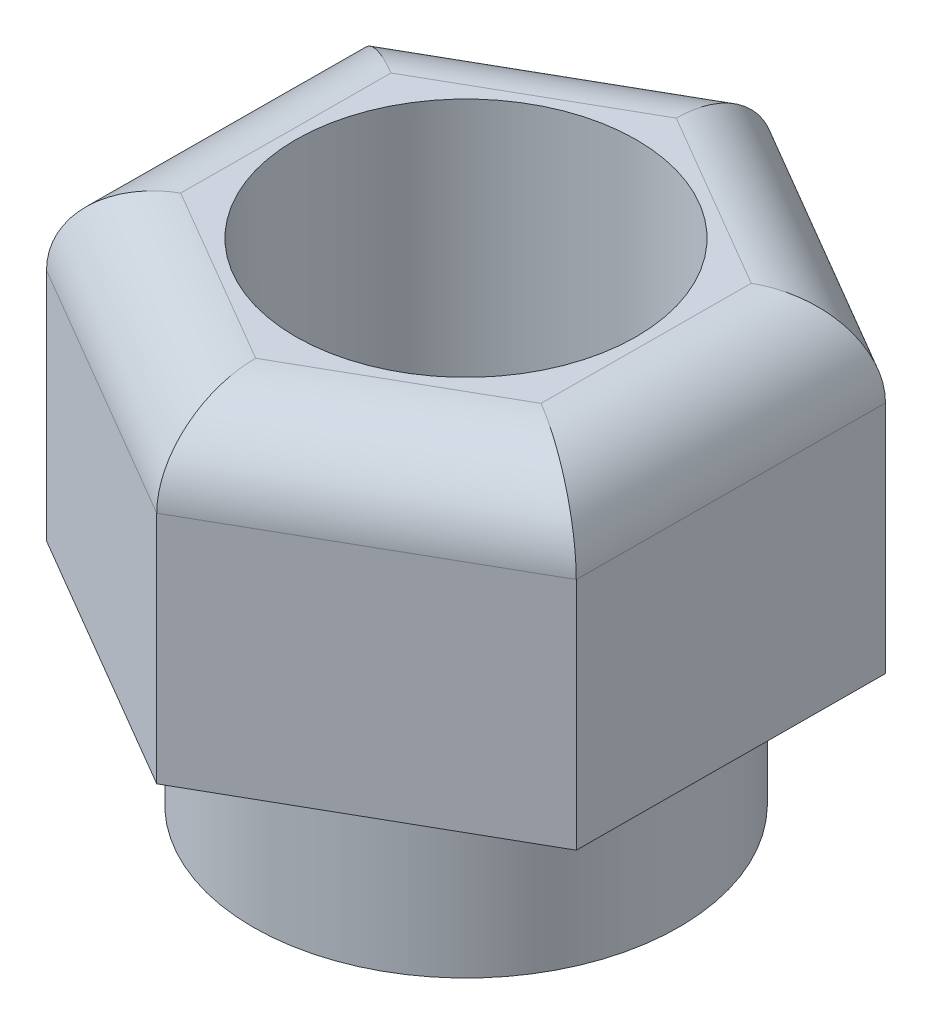
SolidWorks part; units mm, degrees
ref_plane "Front Plane" through (0, 0, 0) normal (0, 0, 1) x (1, 0, 0)
ref_plane "Top Plane" through (0, 0, 0) normal (0, 1, 0) x (1, 0, 0)
ref_plane "Right Plane" through (0, 0, 0) normal (1, 0, 0) x (0, 0, -1)
sketch "Sketch1" plane through (0, 0, 0) normal (0, 1, 0) x (1, 0, 0)
  circle A0 centre (0, 0) radius 10
  dimension "D1" = 20
extrude "Boss-Extrude1" add sketch "Sketch1" along normal blind 8
sketch "Sketch2" plane through (0, 8, 0) normal (0, 1, 0) x (1, 0, 0)
  line L1 (12.4601, -7.2856) -> (12.5395, 7.148)
  line L2 (12.5395, 7.148) -> (0.0794, 14.4335)
  line L3 (0.0794, 14.4335) -> (-12.4601, 7.2856)
  line L4 (-12.4601, 7.2856) -> (-12.5395, -7.148)
  line L5 (-12.5395, -7.148) -> (-0.0794, -14.4335)
  line L6 (-0.0794, -14.4335) -> (12.4601, -7.2856)
  circle A0 centre (0, 0) radius 12.5 construction
  dimension "D1" = 25
extrude "Boss-Extrude2" add sketch "Sketch2" along normal blind 15
sketch "Sketch3" plane through (0, 0, 0) normal (0, -1, 0) x (1, 0, 0)
  circle A0 centre (0, 0) radius 8
  dimension "D1" = 16
extrude "Cut-Extrude1" cut sketch "Sketch3" against normal up to next
fillet "Fillet1" radius 4 6 edges at (-6.3095, 23, 10.7908) (-12.4998, 23, -0.0688) (-6.1903, 23, -10.8595) (6.3095, 23, -10.7908) (12.4998, 23, 0.0688) (6.1903, 23, 10.8595)
